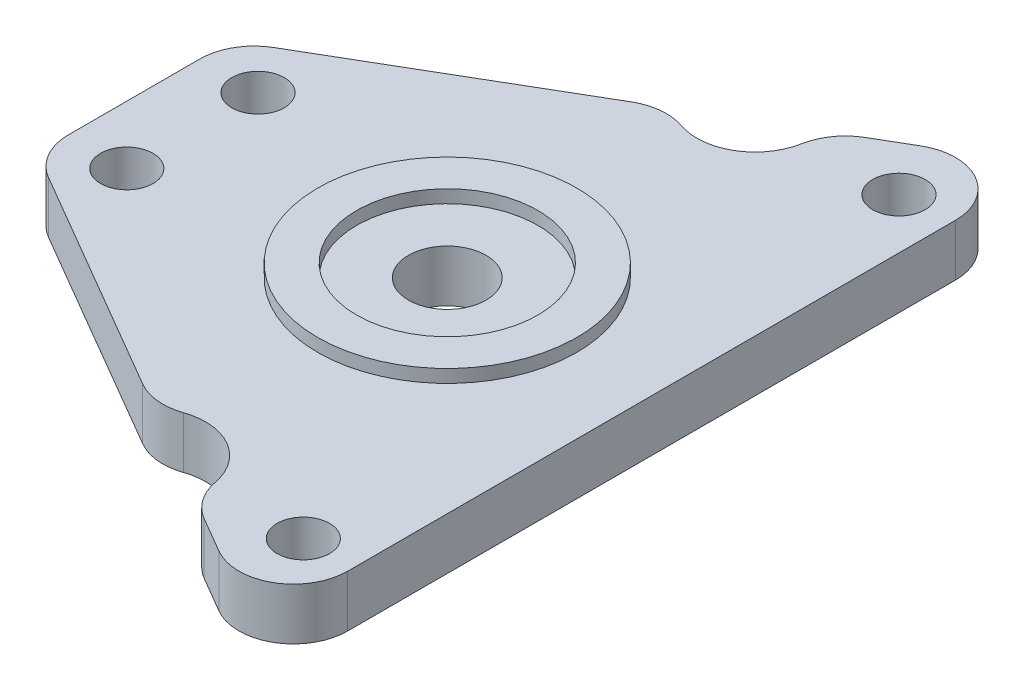
SolidWorks part; units mm, degrees
ref_plane "Front Plane" through (0, 0, 0) normal (0, 0, 1) x (1, 0, 0)
ref_plane "Top Plane" through (0, 0, 0) normal (0, 1, 0) x (1, 0, 0)
ref_plane "Right Plane" through (0, 0, 0) normal (1, 0, 0) x (0, 0, -1)
sketch "Sketch1" plane through (0, 0, 0) normal (0, 1, 0) x (1, 0, 0)
  line L5 (0, -7.478) -> (0, 7.478)
  line L6 (0, 7.478) -> (21.5553, 20.0451)
  line L7 (39.9601, 30.7754) -> (39.9601, -30.7753)
  line L8 (0, -7.478) -> (21.5553, -20.0451)
  line L10 (28.897, -24.3254) -> (39.9601, -30.7753)
  line L12 (28.897, 24.3254) -> (39.9601, 30.7754)
  arc A5 (28.897, -24.3254) -> (21.5553, -20.0451) centre (24.4801, -23.465) ccw
  arc A6 (21.5553, 20.0451) -> (28.897, 24.3254) centre (24.4801, 23.465) ccw
  point P0 (0, 0)
  dimension "D5" = 12.8059
  dimension "D6" = 120.243
  dimension "D14" = 4.5
  dimension "D2" = 14.956
  dimension "D3" = 120.243
  dimension "D4" = 24.9512
  dimension "D7" = 39.9601
extrude "Boss-Extrude1" add sketch "Sketch1" along normal blind 4
fillet "Fillet1" radius 4.2 8 edges at (0, 2, -7.478) (28.897, 2, 24.3254) (21.5553, 2, 20.0451) (0, 2, 7.478) (39.9601, 2, 30.7753) (39.9601, 2, -30.7754) (28.897, 2, -24.3254) (21.5553, 2, -20.0451)
sketch "Sketch3" plane through (0, 4, 0) normal (0, 1, 0) x (1, 0, 0)
  line L0 (0, 5.065) -> (0, -5.065) construction
  line L1 (4.5, 5.065) -> (4.5, -5.065) construction
  circle A0 centre (24.18, 0) radius 3
  circle A1 centre (36.06, -22.995) radius 2.025
  circle A2 centre (36.06, 22.995) radius 2.025
  circle A3 centre (4.5, 5.065) radius 2.025
  circle A4 centre (4.5, -5.065) radius 2.025
  point P12 (4.5, 0)
  dimension "D1" = 4.05
  dimension "D2" = 6
  dimension "D7" = 17.93
  dimension "D3" = 4.5
  dimension "D4" = 10.13
  dimension "D5" = 19.68
  dimension "D6" = 11.88
  dimension "D8" = 17.93
extrude "Cut-Extrude1" cut sketch "Sketch3" against normal through all
sketch "Sketch2" plane through (0, 4, 0) normal (0, 1, 0) x (1, 0, 0)
  circle A0 centre (24.18, 0) radius 10
  circle A1 centre (24.18, 0) radius 7
  dimension "D1" = 14
  dimension "D2" = 20
extrude "Boss-Extrude2" add sketch "Sketch2" along normal blind 1
